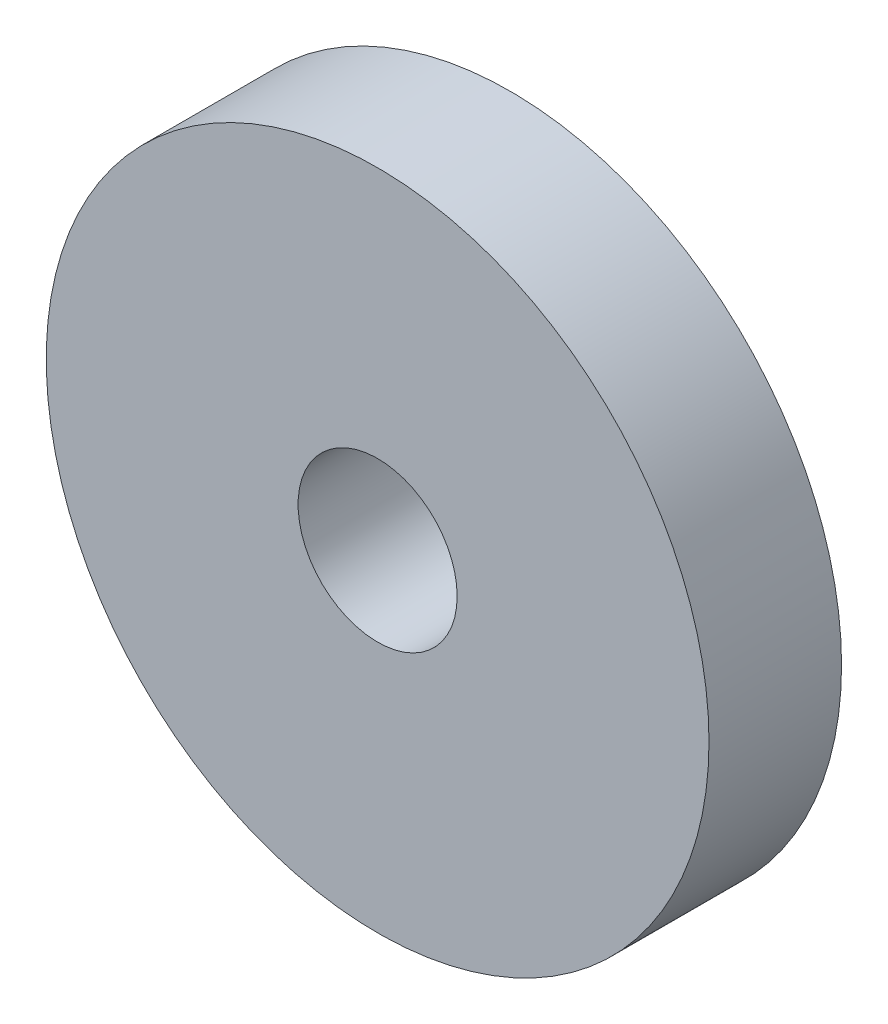
SolidWorks part; units mm, degrees
ref_plane "Front Plane" through (0, 0, 0) normal (0, 0, 1) x (1, 0, 0)
ref_plane "Top Plane" through (0, 0, 0) normal (0, 1, 0) x (1, 0, 0)
ref_plane "Right Plane" through (0, 0, 0) normal (1, 0, 0) x (0, 0, -1)
sketch "Sketch1" plane through (0, 0, 0) normal (0, 0, 1) x (1, 0, 0)
  circle A0 centre (0, 0) radius 3
  circle A1 centre (0, 0) radius 12.5
  dimension "D1" = 6
  dimension "D2" = 25
extrude "Boss-Extrude1" add sketch "Sketch1" along normal blind 5
